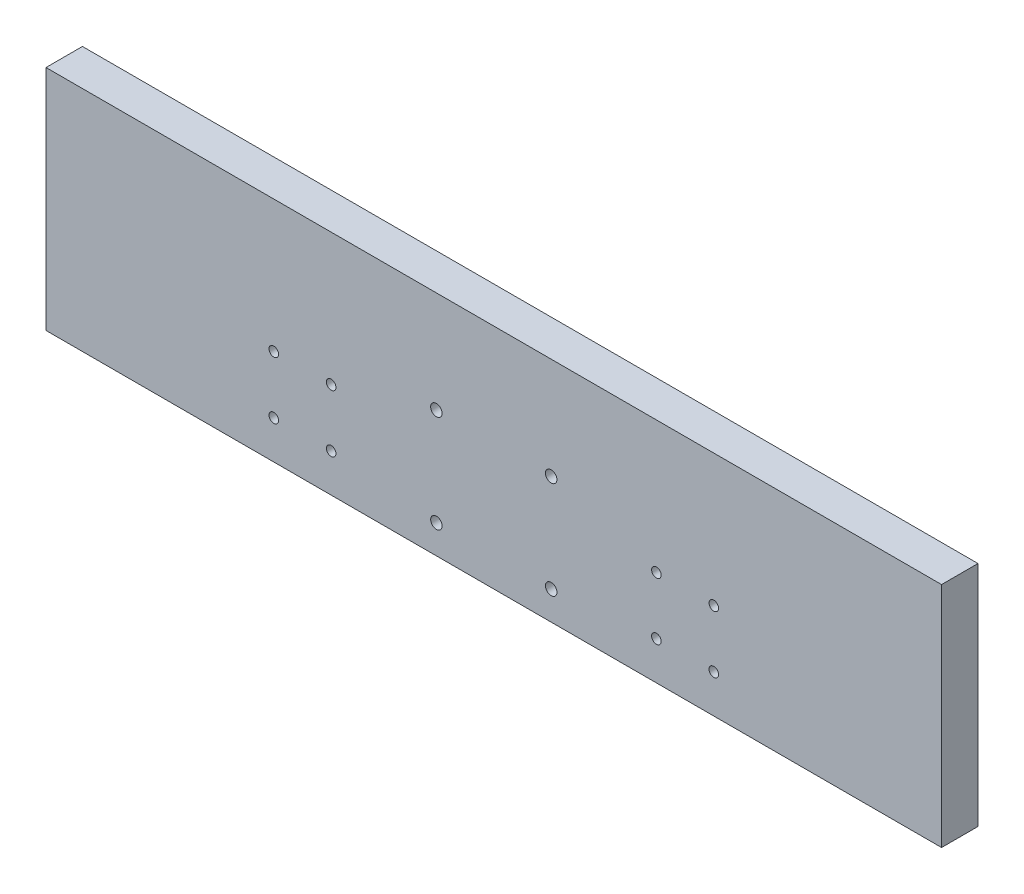
SolidWorks part; units mm, degrees
ref_plane "Front Plane" through (0, 0, 0) normal (0, 0, 1) x (1, 0, 0)
ref_plane "Top Plane" through (0, 0, 0) normal (0, 1, 0) x (1, 0, 0)
ref_plane "Right Plane" through (0, 0, 0) normal (1, 0, 0) x (0, 0, -1)
sketch "Sketch1" plane through (0, 0, 0) normal (0, 0, 1) x (1, 0, 0)
  line L1 (234.05, 0) -> (-234.05, 0)
  line L2 (234.05, 0) -> (234.05, 119.05)
  line L3 (234.05, 119.05) -> (-234.05, 119.05)
  line L4 (-234.05, 0) -> (-234.05, 119.05)
  line L5 (-234.05, 119.05) -> (234.05, 119.05) construction
  dimension "D1" = 119.05
  dimension "D2" = 468.1
extrude "Boss-Extrude1" add sketch "Sketch1" along normal blind 19.05
hole_wizard "M5 Clearance Hole1" positions "Sketch2" profile "Sketch3" hole size "M5" standard "ANSI Metric"
sketch "Sketch2" plane through (0, 0, 0) normal (0, 0, -1) x (-1, 0, 0)
  point P0 (-115, 20)
  point P3 (-115, 50)
  point P6 (-85, 50)
  point P9 (-85, 20)
  point P12 (85, 20)
  point P15 (85, 50)
  point P18 (115, 50)
  point P21 (115, 20)
  point P27 (0, 0)
sketch "Sketch3" plane through (115, 20, 0) normal (1, 0, 0) x (0, 1, 0)
  line L0 (0, 0) -> (0, 30)
  line L1 (0, 30) -> (2.5, 28.4978)
  line L2 (2.5, 28.4978) -> (2.5, 0)
  line L5 (2.5, 0) -> (0, 0)
  line L10 (0, 30) -> (-2.5, 28.4978) construction
  line L11 (0, -6.35) -> (0, 107.95) construction
  dimension "Hole Dia." = 5
  dimension "Hole Depth" = 30
  dimension "Drill Angle" = 118
sketch "Sketch4" plane through (0, 0, 0) normal (0, 0, -1) x (-1, 0, 0)
  circle A0 centre (-30, 15) radius 3 construction
  circle A1 centre (-30, 66) radius 3 construction
  circle A2 centre (30, 66) radius 3 construction
  circle A3 centre (30, 15) radius 3 construction
  circle A4 centre (-30, 15) radius 3
  circle A5 centre (-30, 66) radius 3
  circle A6 centre (30, 66) radius 3
  circle A7 centre (30, 15) radius 3
hole_wizard "M5 Clearance Hole2" positions "Sketch5" profile "Sketch6" hole size "M5" standard "ANSI Metric"
sketch "Sketch5" plane through (0, 0, 0) normal (0, 0, -1) x (-1, 0, 0)
  point P0 (30, 15)
  point P3 (30, 66)
  point P6 (-30, 15)
  point P9 (-30, 66)
sketch "Sketch6" plane through (-30, 15, 0) normal (1, 0, 0) x (0, 1, 0)
  line L0 (0, 0) -> (0, 30)
  line L1 (0, 30) -> (3, 28.1974)
  line L2 (3, 28.1974) -> (3, 0)
  line L5 (3, 0) -> (0, 0)
  line L10 (0, 30) -> (-3, 28.1974) construction
  line L11 (0, -6.35) -> (0, 107.95) construction
  dimension "Hole Dia." = 6
  dimension "Hole Depth" = 30
  dimension "Drill Angle" = 118
